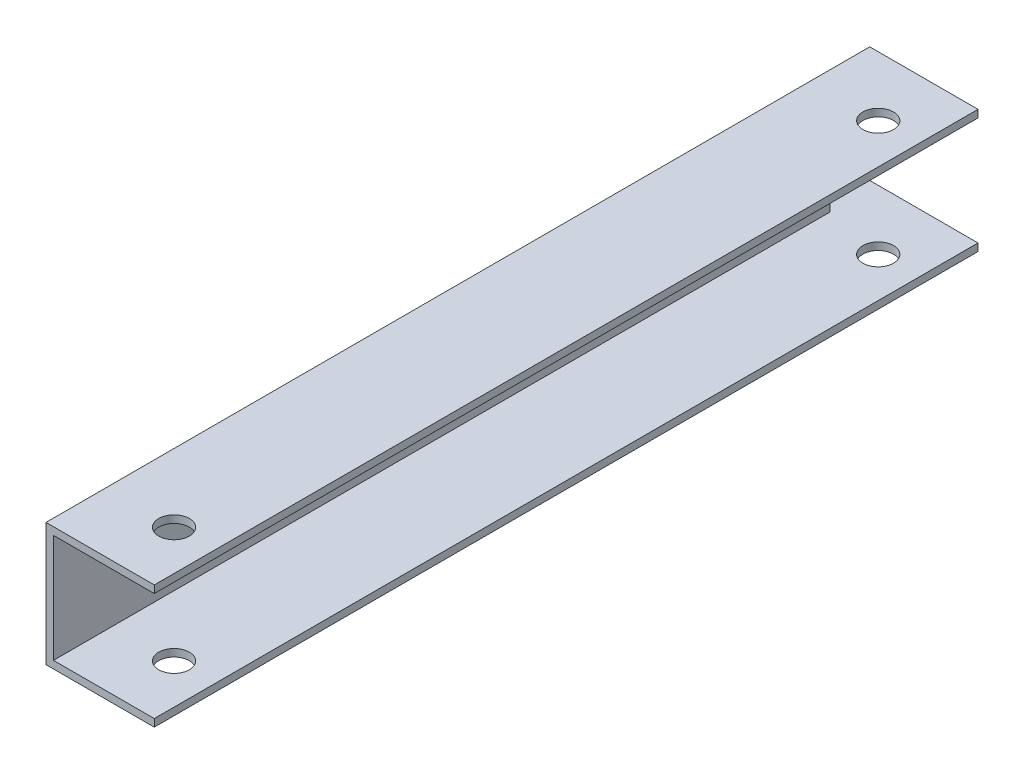
SolidWorks part; units mm, degrees
ref_plane "Alzado" through (0, 0, 0) normal (0, 0, 1) x (1, 0, 0)
ref_plane "Planta" through (0, 0, 0) normal (0, 1, 0) x (1, 0, 0)
ref_plane "Vista lateral" through (0, 0, 0) normal (1, 0, 0) x (0, 0, -1)
sketch "Croquis1" plane through (0, 0, 0) normal (0, 0, 1) x (1, 0, 0)
  line L0 (23, 23) -> (-19.825, 23)
  line L1 (-19.825, 23) -> (-19.825, -23)
  line L2 (-19.825, -23) -> (23, -23)
  line L3 (23, -23) -> (23, -26.175)
  line L4 (23, -26.175) -> (-23, -26.175)
  line L5 (-23, -26.175) -> (-23, 26.175)
  line L6 (-23, 26.175) -> (23, 26.175)
  line L7 (23, 26.175) -> (23, 23)
  line L8 (4.9953, 0) -> (-27.8663, 0) construction
  line L9 (0, -5.8991) -> (0, 13.2585) construction
  point P11 (-19.825, 0)
  point P14 (0, 26.175)
  dimension "D1" = 3.175
  dimension "D2" = 23
  dimension "D3" = 3.175
  dimension "D4" = 46
extrude "Saliente-Extruir1" add sketch "Croquis1" along normal mid plane 350
sketch "Croquis2" plane through (0, -26.175, 0) normal (0, -1, 0) x (1, 0, 0)
  line L0 (0, 155.2457) -> (0, -11.6513) construction
  line L1 (52.5458, 0) -> (-47.5924, 0) construction
  line L2 (-23, 175) -> (23, 175) construction
  circle A0 centre (6, 149.6) radius 6.5
  circle A1 centre (6, -149.6) radius 6.5
  dimension "D1" = 13
  dimension "D2" = 25.4
  dimension "D3" = 6
extrude "Cortar-Extruir1" cut sketch "Croquis2" against normal blind 300
sketch "Croquis3" plane through (-23, 0, 0) normal (-1, 0, 0) x (0, 0, 1)
  line L5 (-175, 26.175) -> (-175, -26.175) construction
  line L6 (-175, 23) -> (-155, 23)
  line L7 (-175, 23) -> (-175, -23)
  line L8 (-175, -23) -> (-155, -23)
  line L9 (-155, 23) -> (-155, -23)
  line L10 (175, 26.175) -> (-175, 26.175) construction
  line L11 (175, -26.175) -> (-175, -26.175) construction
  dimension "D1" = 20
  dimension "D2" = 3.175
  dimension "D3" = 3.175
extrude "Cortar-Extruir2" cut sketch "Croquis3" against normal blind 10
